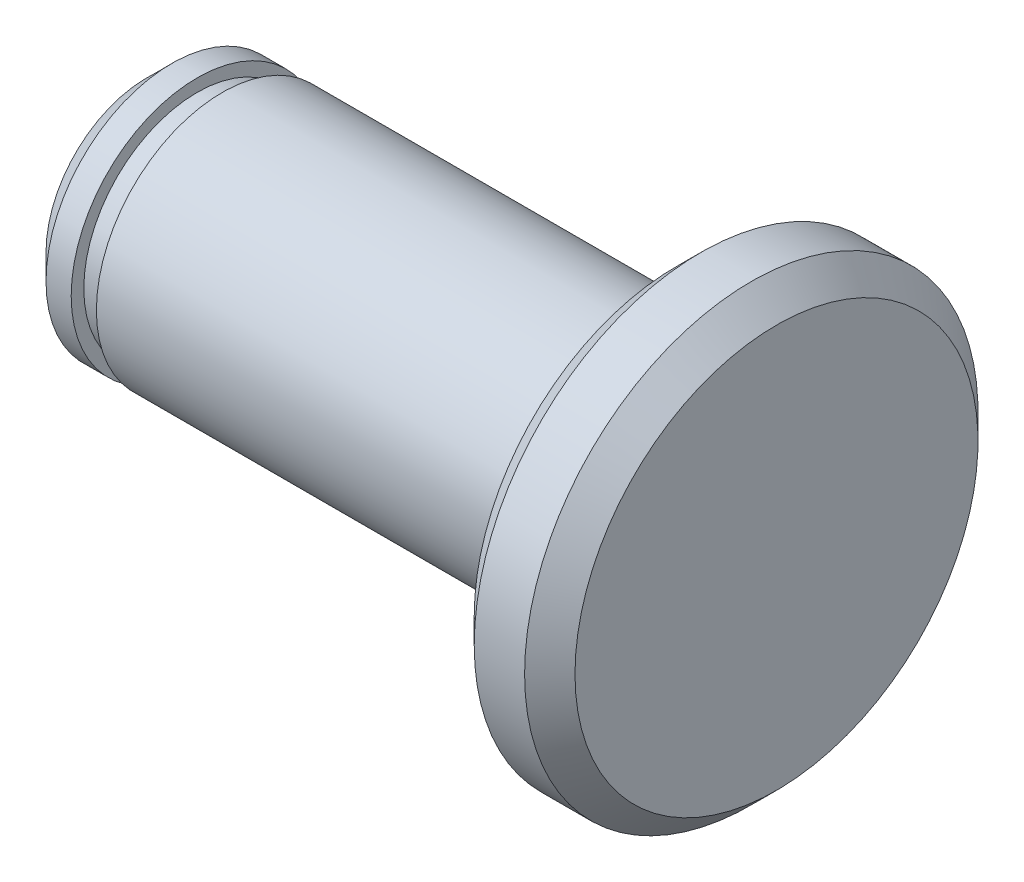
SolidWorks part; units mm, degrees
ref_plane "Front Plane" through (0, 0, 0) normal (1, 0, 0) x (0, 1, 0)
ref_plane "Top Plane" through (0, 0, 0) normal (0, 0, 1) x (0, 1, 0)
ref_plane "Right Plane" through (0, 0, 0) normal (0, 1, 0) x (-1, 0, 0)
sketch "Sketch1" plane through (0, 0, 0) normal (0, 1, 0) x (-1, 0, 0)
  line L0 (0, 0) -> (0, 9) construction
  line L1 (-1, 9) -> (-3, 9)
  line L2 (-4, 8) -> (-4, 0)
  line L3 (-4, 0) -> (21, 0) construction
  line L4 (21, 0) -> (21, 4)
  line L5 (20, 5) -> (19, 5)
  line L6 (0, 8) -> (0, 5)
  line L7 (19, 5) -> (19, 4.5)
  line L8 (19, 4.5) -> (18, 4.5)
  line L9 (18, 4.5) -> (18, 5)
  line L10 (18, 5) -> (0, 5)
  line L11 (21, 4) -> (20, 5)
  line L12 (-1, 9) -> (0, 8)
  line L13 (-3, 9) -> (-4, 8)
  line L14 (21, 0) -> (-4, 0)
  point P4 (-4, 9)
  point P7 (21, 5)
  dimension "D1" = 10
  dimension "D2" = 18
  dimension "D3" = 4
  dimension "D4" = 21
  dimension "D5" = 0.5
  dimension "D6" = 18
  dimension "D7" = 1
revolve "Revolve1" add sketch "Sketch1" angle 360 about L14
